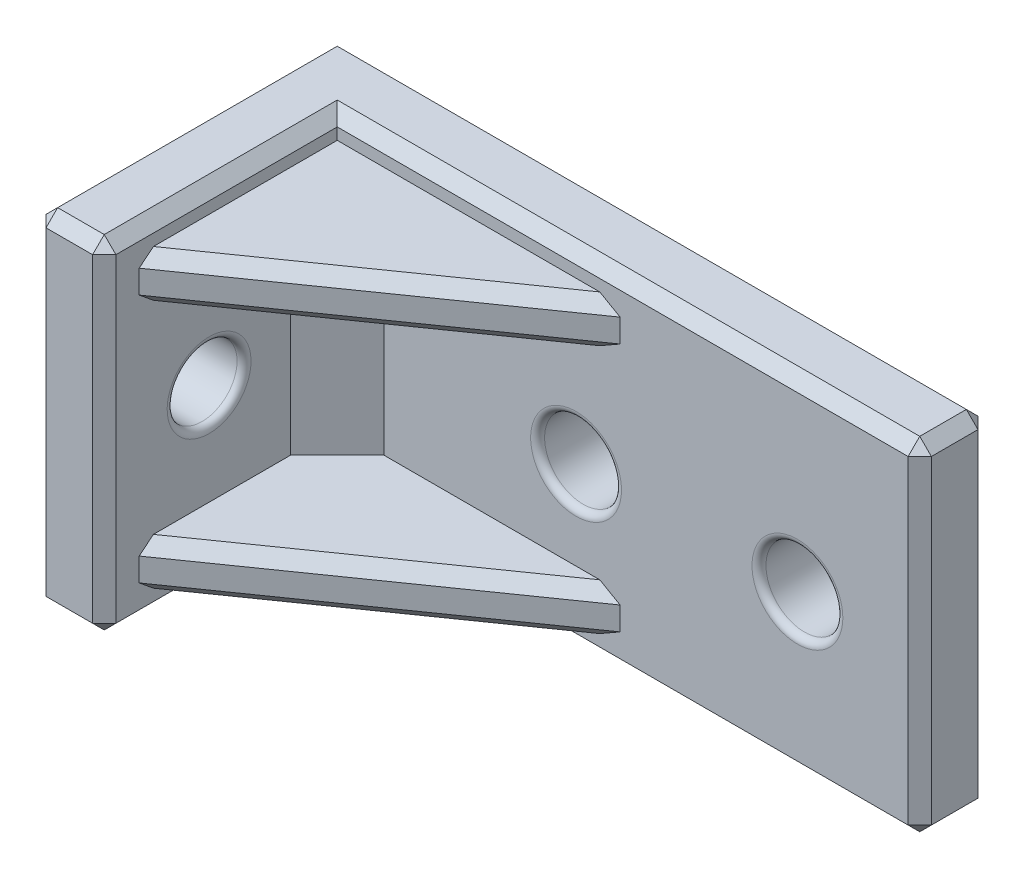
SolidWorks part; units mm, degrees
ref_plane "Plano frontal" through (0, 0, 0) normal (0, 0, 1) x (1, 0, 0)
ref_plane "Plano superior" through (0, 0, 0) normal (0, 1, 0) x (1, 0, 0)
ref_plane "Plano direito" through (0, 0, 0) normal (1, 0, 0) x (0, 0, -1)
sketch "Esboço1" plane through (0, 0, 0) normal (0, 0, 1) x (1, 0, 0)
  line L0 (10, -4.45) -> (10, 4.15)
  line L1 (9.5, 4.65) -> (0.7, 4.65)
  line L2 (0.7, 4.65) -> (0, 5.35)
  line L3 (0, 5.35) -> (-9.5, 5.35)
  line L4 (-10, 4.85) -> (-10, -4.45)
  line L5 (-9.5, -4.95) -> (-7.05, -4.95)
  line L6 (-7.05, -4.95) -> (-6.65, -5.35)
  line L7 (-6.65, -5.35) -> (-2.85, -5.35)
  line L8 (-2.85, -5.35) -> (-2.45, -4.95)
  line L9 (-2.45, -4.95) -> (2.45, -4.95)
  line L10 (2.45, -4.95) -> (2.85, -5.35)
  line L11 (2.85, -5.35) -> (6.65, -5.35)
  line L12 (6.65, -5.35) -> (7.05, -4.95)
  line L13 (7.05, -4.95) -> (9.5, -4.95)
  circle A0 centre (4.75, -2.55) radius 1.5
  circle A1 centre (-4.75, -2.55) radius 1.5
  arc A2 (9.5, -4.95) -> (10, -4.45) centre (9.5, -4.45) ccw
  arc A3 (10, 4.15) -> (9.5, 4.65) centre (9.5, 4.15) ccw
  arc A4 (-9.5, 5.35) -> (-10, 4.85) centre (-9.5, 4.85) ccw
  arc A5 (-10, -4.45) -> (-9.5, -4.95) centre (-9.5, -4.45) ccw
sketch "Esboço2" plane through (0, 0, 0) normal (0, 0, 1) x (1, 0, 0)
  line L1 (-18, 5.35) -> (10, 5.35)
  line L4 (10, 5.35) -> (10, -9.35)
  line L5 (0, 5.35) -> (-9.5, 5.35) construction
  line L6 (10, -4.45) -> (10, 4.15) construction
  line L10 (-18, -9.35) -> (10, -9.35)
  line L11 (-6.65, -5.35) -> (-2.85, -5.35) construction
  line L12 (-18, 5.35) -> (-18, -9.35)
  circle A4 centre (-4.75, -2.55) radius 1.65
  circle A5 centre (4.75, -2.55) radius 1.65
  dimension "D4" = 3.3
  dimension "D5" = 3.3
  dimension "D1" = 9.5
  dimension "D2" = 0
  dimension "D3" = 0
  dimension "D6" = 4
  dimension "D7" = 7.9
  dimension "D8" = 7.9
  dimension "D9" = 5.25
  dimension "D10" = 28
extrude "Ressalto-extrusão1" add sketch "Esboço2" along normal blind 3
sketch "Esboço3" plane through (0, 0, 3) normal (0, 0, 1) x (1, 0, 0)
  line L0 (-18, -9.35) -> (10, -9.35) construction
  line L7 (-18, 5.35) -> (-15, 5.35)
  line L8 (-18, 5.35) -> (-18, -9.35)
  line L9 (-18, -9.35) -> (-15, -9.35)
  line L10 (-15, 5.35) -> (-15, -9.35)
  dimension "D1" = 3
extrude "Ressalto-extrusão2" add sketch "Esboço3" along normal blind 10
sketch "Esboço4" plane through (-15, 0, 0) normal (1, 0, 0) x (0, 0, -1)
  line L4 (-13, -2) -> (-8.5, -2) construction
  line L5 (-13, -9.35) -> (-13, 5.35) construction
  circle A0 centre (-8.5, -2) radius 1.5
  point P6 (0, 0)
  dimension "D2" = 3
  dimension "D1" = 4.5
extrude "Corte-extrusão1" cut sketch "Esboço4" against normal blind 10
fillet "Filete1" radius 0.3 6 edges at (6.4, -2.55, 0) (6.4, -2.55, 3) (-3.1, -2.55, 0) (-3.1, -2.55, 3) (-18, -2, 7) (-15, -0.5, 8.5)
ref_plane "Plano1" through (0, 4.35, 0) normal (0, 1, 0) x (1, 0, 0)
sketch "Esboço5" plane through (0, 4.35, 0) normal (0, 1, 0) x (1, 0, 0)
  line L1 (-15, -3) -> (-2.8607, -3)
  line L4 (-2.8607, -3) -> (-15, -11.5)
  line L7 (-15, -3) -> (-15, -11.5)
  dimension "D1" = 35
  dimension "D2" = 8.5
extrude "Ressalto-extrusão3" add sketch "Esboço5" against normal blind 2
ref_plane "Plano2" through (0, -8.35, 0) normal (0, -1, 0) x (-1, 0, 0)
sketch "Esboço7" plane through (0, -8.35, 0) normal (0, -1, 0) x (-1, 0, 0)
  line L3 (15, -11.5) -> (15, -3)
  line L4 (15, -3) -> (2.8607, -3)
  line L5 (2.8607, -3) -> (15, -11.5)
  line L6 (15, -11.5) -> (15, -3)
  line L7 (15, -3) -> (2.8607, -3)
  line L8 (2.8607, -3) -> (15, -11.5)
  dimension "D1" = 0
extrude "Ressalto-extrusão4" add sketch "Esboço7" against normal blind 2
chamfer "Chanfro4" distance 0.5 angle 45 20 edges at (-15, -2, 13) (-18, -2, 13) (-18, -9.35, 6.5) (-16.5, -9.35, 13) (-15, -9.35, 8) (-2.5, -9.35, 3) (-4, -9.35, 0) (-2.5, 5.35, 3) (-15, 5.35, 8) (-16.5, 5.35, 13) (-18, 5.35, 6.5) (-4, 5.35, 0) (10, -9.35, 1.5) (10, -2, 3) (10, 5.35, 1.5) (10, -2, 0) (-8.9304, -8.35, 7.25) (-8.9304, -6.35, 7.25) (-8.9304, 2.35, 7.25) (-8.9304, 4.35, 7.25)
chamfer "Chanfro6" distance 2 angle 45 1 edges at (-15, -2, 3)
